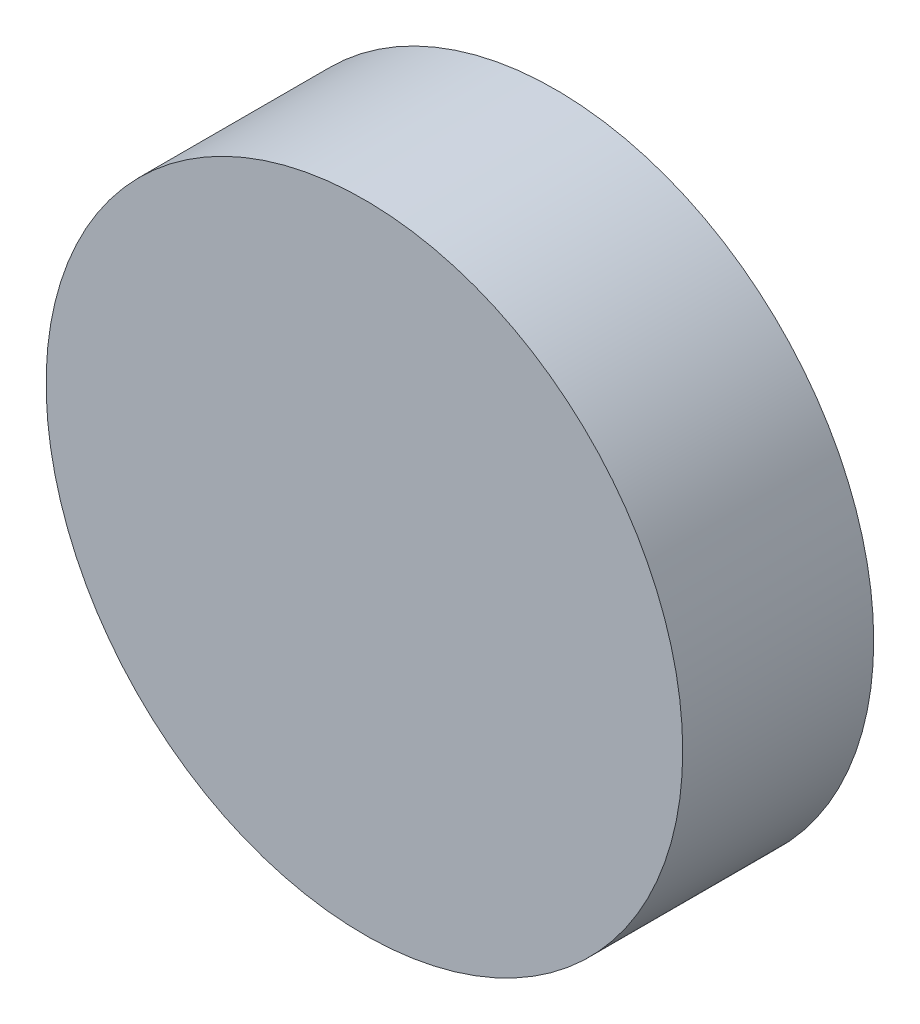
SolidWorks part; units mm, degrees
ref_plane "Alzado" through (0, 0, 0) normal (0, 0, 1) x (1, 0, 0)
ref_plane "Planta" through (0, 0, 0) normal (0, 1, 0) x (1, 0, 0)
ref_plane "Vista lateral" through (0, 0, 0) normal (1, 0, 0) x (0, 0, -1)
sketch "Croquis1" plane through (0, 0, 0) normal (0, 0, 1) x (1, 0, 0)
  circle A0 centre (0, 0) radius 5
  dimension "D1" = 10
extrude "Saliente-Extruir1" add sketch "Croquis1" along normal blind 3
